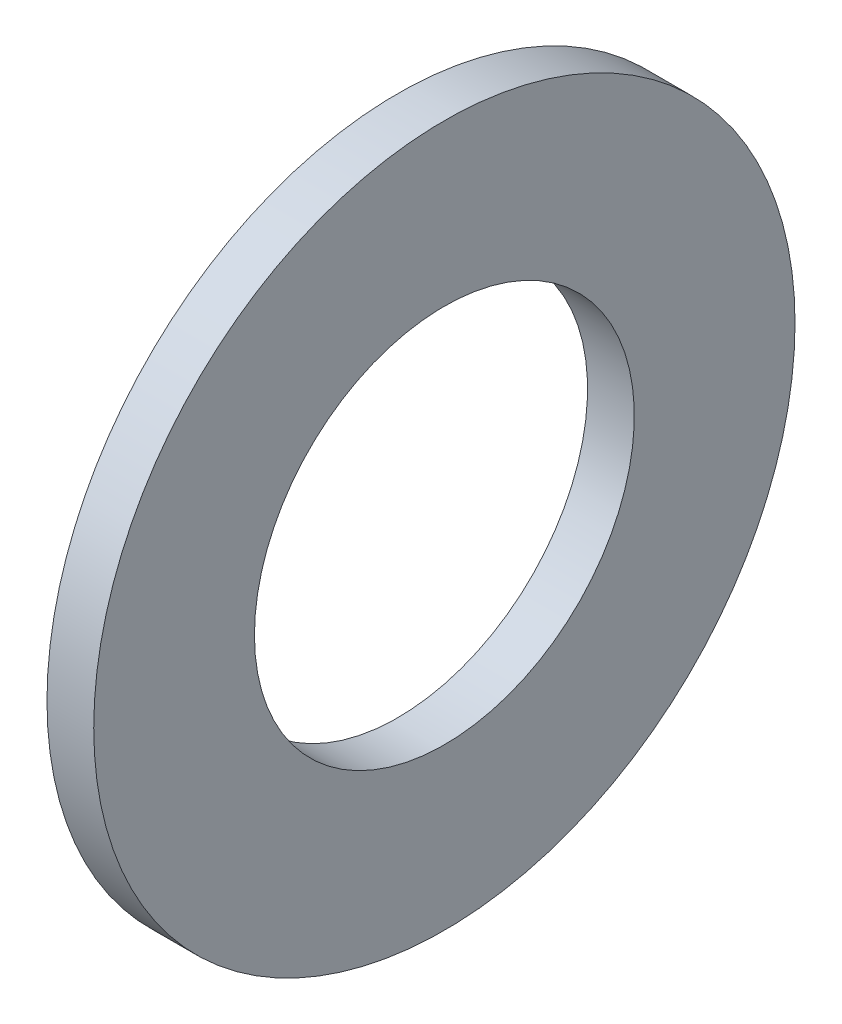
SolidWorks part; units mm, degrees
ref_plane "Plane1" through (0, 0, 0) normal (0, 0, 1) x (1, 0, 0)
ref_plane "Plane2" through (0, 0, 0) normal (0, 1, 0) x (1, 0, 0)
ref_plane "Plane3" through (0, 0, 0) normal (1, 0, 0) x (0, 0, -1)
sketch "Sketch1" plane through (0, 0, 0) normal (0, 0, 1) x (1, 0, 0)
  line L0 (-34.925, 0) -> (9.525, 0) construction
  line L1 (0, 3.25) -> (0, 6)
  line L2 (0, 6) -> (-0.8, 6)
  line L3 (-0.8, 6) -> (-0.8, 3.25)
  line L4 (-0.8, 3.25) -> (0, 3.25)
  dimension "Thickness" = 0.8
  dimension "Inside_dia" = 6.5
  dimension "Outside_dia" = 12
revolve "Base-Revolve" add sketch "Sketch1" angle 360 about L0
